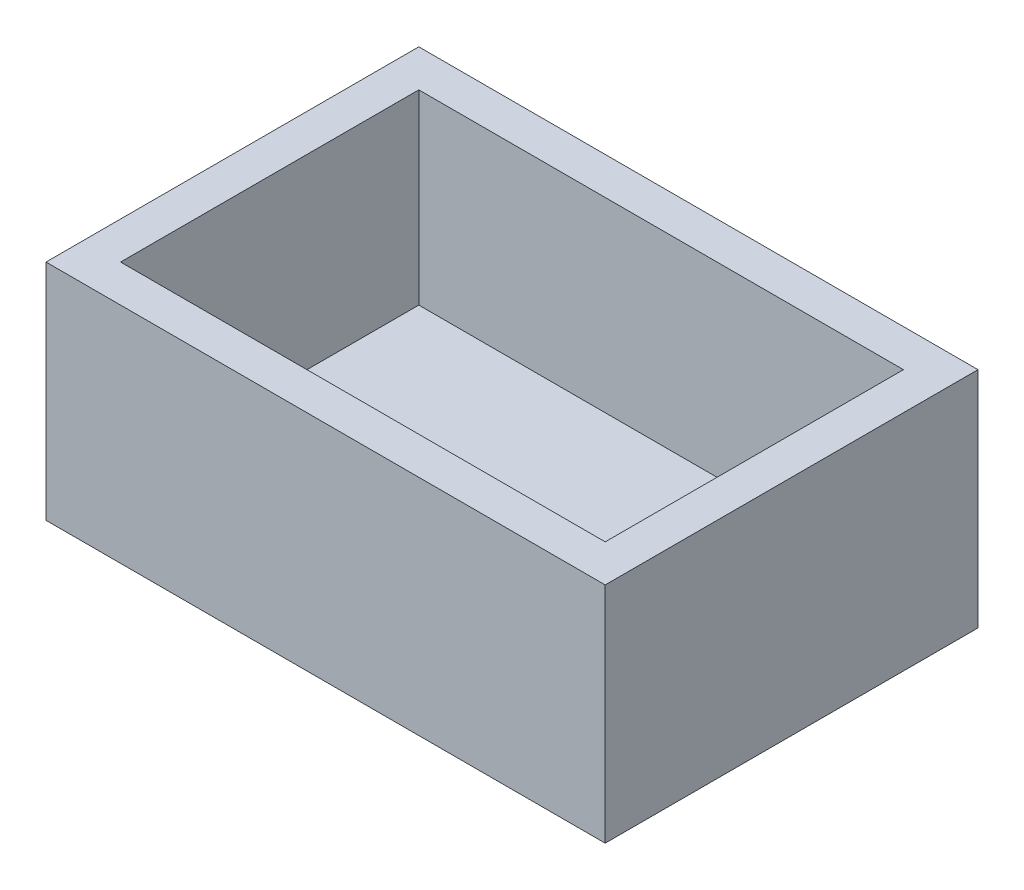
SolidWorks part; units mm, degrees
ref_plane "Front Plane" through (0, 0, 0) normal (0, 0, 1) x (1, 0, 0)
ref_plane "Top Plane" through (0, 0, 0) normal (0, 1, 0) x (1, 0, 0)
ref_plane "Right Plane" through (0, 0, 0) normal (1, 0, 0) x (0, 0, -1)
sketch "Sketch1" plane through (0, 0, 0) normal (0, 1, 0) x (1, 0, 0)
  line L1 (-75, 50) -> (75, 50)
  line L2 (-75, 50) -> (-75, -50)
  line L3 (-75, -50) -> (75, -50)
  line L4 (75, 50) -> (75, -50)
  line L5 (-75, 50) -> (75, -50) construction
  line L6 (-75, -50) -> (75, 50) construction
  point P0 (0, 0)
  dimension "D1" = 150
  dimension "D2" = 100
extrude "Boss-Extrude1" add sketch "Sketch1" along normal blind 60
sketch "Sketch2" plane through (0, 60, 0) normal (0, 1, 0) x (1, 0, 0)
  line L4 (75, -50) -> (75, 50)
  line L5 (75, 50) -> (-75, 50)
  line L6 (-75, 50) -> (-75, -50)
  line L7 (-75, -50) -> (75, -50)
  line L8 (75, -50) -> (75, 50)
  line L9 (75, 50) -> (-75, 50)
  line L10 (-75, 50) -> (-75, -50)
  line L11 (-75, -50) -> (75, -50)
  line L16 (65, -40) -> (65, 40)
  line L17 (65, 40) -> (-65, 40)
  line L18 (-65, 40) -> (-65, -40)
  line L19 (-65, -40) -> (65, -40)
  line L20 (65, -40) -> (65, 40)
  line L21 (65, 40) -> (-65, 40)
  line L22 (-65, 40) -> (-65, -40)
  line L23 (-65, -40) -> (65, -40)
  dimension "D2" = 10
  dimension "D1" = 0
extrude "Cut-Extrude1" cut sketch "Sketch2" against normal blind 50 contours L20 L21 L22 L23
